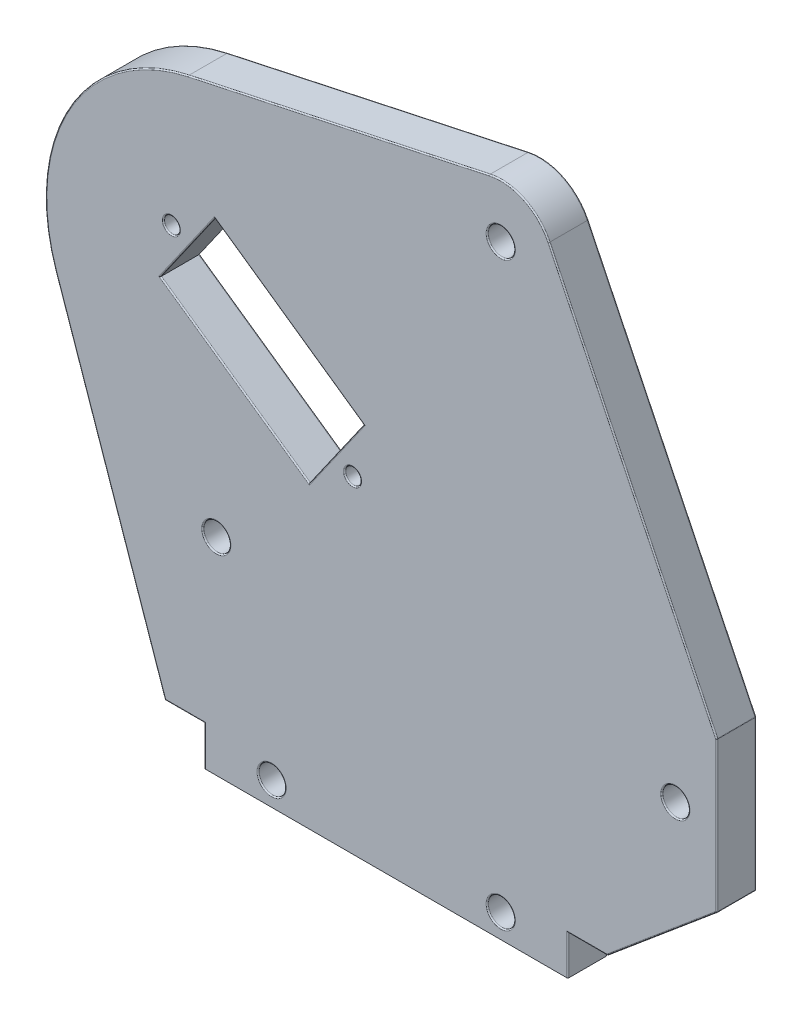
SolidWorks part; units mm, degrees
material "AISI 1020"
ref_plane "Front Plane" through (0, 0, 0) normal (0, 0, 1) x (1, 0, 0)
ref_plane "Top Plane" through (0, 0, 0) normal (0, 1, 0) x (1, 0, 0)
ref_plane "Right Plane" through (0, 0, 0) normal (1, 0, 0) x (0, 0, -1)
sketch "Sketch1" plane through (0, 0, 0) normal (0, 0, 1) x (1, 0, 0)
  line L0 (41.85, 40.6215) -> (20.6106, 84.4605) construction
  line L1 (41.85, 21.6215) -> (41.85, 40.6215) construction
  line L2 (28, 10) -> (41.85, 21.6215) construction
  line L3 (23, 10) -> (28, 10) construction
  line L4 (23, 0) -> (23, 10) construction
  line L5 (-23, 0) -> (23, 0) construction
  line L6 (-23, 0) -> (-23, 10) construction
  line L7 (-23, 10) -> (-28, 10) construction
  line L8 (-28, 10) -> (-41.8438, 50.1182) construction
  line L9 (-25.0297, 79.9436) -> (13.0723, 88.1382) construction
  line L10 (41.85, 40.6215) -> (20.6106, 84.4605)
  line L11 (41.85, 21.6215) -> (41.85, 40.6215)
  line L12 (28, 10) -> (41.85, 21.6215)
  line L13 (23, 10) -> (28, 10)
  line L14 (23, 0) -> (23, 10)
  line L15 (-23, 0) -> (23, 0)
  line L16 (-23, 0) -> (-23, 10)
  line L17 (-23, 10) -> (-28, 10)
  line L18 (-28, 10) -> (-41.8438, 50.1182)
  line L19 (-25.0297, 79.9436) -> (13.0723, 88.1382)
  line L20 (0, 0) -> (0, 14.8705) construction
  line L21 (-21.6935, 65.9364) -> (-28.5764, 56.1065)
  line L22 (-21.6935, 65.9364) -> (-2.853, 52.7441)
  line L23 (-28.5764, 56.1065) -> (-9.7359, 42.9143)
  line L24 (-2.853, 52.7441) -> (-9.7359, 42.9143)
  line L25 (-6.2944, 47.8292) -> (-25.1349, 61.0215) construction
  line L26 (-15.7147, 54.4253) -> (-19.1561, 49.5104) construction
  arc A0 (20.6106, 84.4605) -> (13.0723, 88.1382) centre (14.5, 81.5) ccw construction
  arc A1 (-25.0297, 79.9436) -> (-41.8438, 50.1182) centre (-20.22, 57.58) ccw construction
  arc A2 (20.6106, 84.4605) -> (13.0723, 88.1382) centre (14.5, 81.5) ccw
  arc A3 (-25.0297, 79.9436) -> (-41.8438, 50.1182) centre (-20.22, 57.58) ccw
  circle A4 centre (-27.1828, 62.4554) radius 1
  circle A5 centre (-4.2465, 46.3953) radius 1
  point P4 (14.5, 8)
  point P6 (-14.5, 8)
  point P8 (36.6, 31.1215)
  point P10 (-21.5, 31.1215)
  point P12 (14.5, 81.5)
  point P14 (41.85, 31.1215)
  point P27 (-20.22, 57.58)
  dimension "D9" = 2
  dimension "D1" = 5.25
  dimension "D2" = 8
  dimension "D3" = 21.5
  dimension "D4" = 23
  dimension "D5" = 12
  dimension "D6" = 35
  dimension "D7" = 6
  dimension "D8" = 2.5
extrude "Boss-Extrude2" add sketch "Sketch1" along normal blind 5
hole_wizard "M3 Clearance Hole1" positions "Sketch10" profile "Sketch11" hole size "M3" standard "ISO" end condition through all
sketch "Sketch10" plane through (0, 0, 5) normal (0, 0, 1) x (1, 0, 0)
  point P0 (14.5, 81.5)
  point P3 (36.6, 31.1215)
  point P6 (14.5, 8)
  point P9 (-14.5, 8)
  point P12 (-21.5, 31.1215)
sketch "Sketch11" plane through (14.5, 81.5, 5) normal (1, 0, 0) x (0, -1, 0)
  line L0 (0, 0) -> (0, 5)
  line L1 (0, 5) -> (1.7, 5)
  line L2 (1.7, 5) -> (1.7, 0)
  line L5 (1.7, 0) -> (0, 0)
  line L11 (0, -6.35) -> (0, 107.95) construction
  dimension "Thru Hole Dia." = 3.4
  dimension "Thru Hole Depth" = 5
fillet "Fillet1" radius 0.15 52 edges at (16.2, 81.5, 5) (16.2, 81.5, 0) (38.3, 31.1215, 5) (38.3, 31.1215, 0) (16.2, 8, 5) (16.2, 8, 0) (-12.8, 8, 5) (-12.8, 8, 0) (-19.8, 31.1215, 5) (-19.8, 31.1215, 0) (-5.2465, 46.3953, 0) (-5.2465, 46.3953, 5) (-26.1828, 62.4554, 0) (-26.1828, 62.4554, 5) (-12.2732, 59.3402, 0) (-25.1349, 61.0215, 0) (-19.1561, 49.5104, 0) (-6.2944, 47.8292, 0) (-12.2732, 59.3402, 5) (-25.1349, 61.0215, 5) (-19.1561, 49.5104, 5) (-6.2944, 47.8292, 5) (17.4772, 87.6025, 0) (-5.9787, 84.0409, 0) (-40.1467, 68.8136, 0) (-34.9219, 30.0591, 0) (-25.5, 10, 0) (-23, 5, 0) (0, 0, 0) (23, 5, 0) (25.5, 10, 0) (34.925, 15.8108, 0) (41.85, 31.1215, 0) (31.2303, 62.541, 0) (17.4772, 87.6025, 5) (-5.9787, 84.0409, 5) (-40.1467, 68.8136, 5) (-34.9219, 30.0591, 5) (-25.5, 10, 5) (-23, 5, 5) (0, 0, 5) (23, 5, 5) (25.5, 10, 5) (34.925, 15.8108, 5) (41.85, 31.1215, 5) (31.2303, 62.541, 5) (41.85, 40.6215, 2.5) (41.85, 21.6215, 2.5) (28, 10, 2.5) (-23, 0, 2.5) (-28, 10, 2.5) (23, 0, 2.5)
sketch "Sketch13" plane through (0, 0, 5) normal (0, 0, 1) x (1, 0, 0)
  line L0 (22.85, 0) -> (-22.85, 0) construction
  line L1 (-23, 5) -> (23, 5)
  line L2 (-23, 5) -> (-23, 0)
  line L3 (-23, 0) -> (23, 0)
  line L4 (23, 5) -> (23, 0)
  line L5 (-23, 0.15) -> (-23, 10) construction
  line L6 (23, 10) -> (23, 0.15) construction
  dimension "D1" = 5
extrude "Cut-Extrude1" cut sketch "Sketch13" against normal through all
